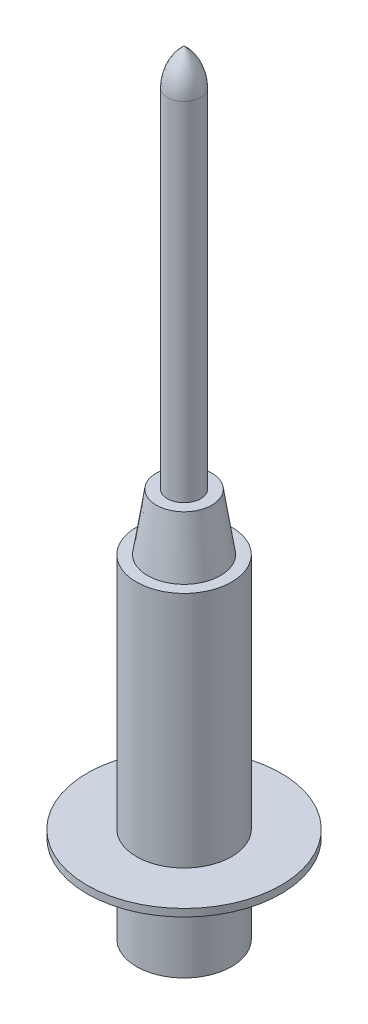
SolidWorks part; units mm, degrees
ref_plane "Front Plane" through (0, 0, 0) normal (0, 0, 1) x (1, 0, 0)
ref_plane "Top Plane" through (0, 0, 0) normal (0, 1, 0) x (1, 0, 0)
ref_plane "Right Plane" through (0, 0, 0) normal (1, 0, 0) x (0, 0, -1)
sketch "Sketch1" plane through (0, 0, 0) normal (0, 0, 1) x (1, 0, 0)
  line L0 (0, 0) -> (4.2806, 0)
  line L2 (4.2806, 29.97) -> (3.2806, 29.97)
  line L5 (1.5, 35.07) -> (1.5, 66.3238)
  line L6 (0, 69.5986) -> (0, 0) construction
  line L8 (4.2806, 0) -> (4.2806, 7.9)
  line L9 (4.2806, 7.9) -> (8.7329, 7.9)
  line L10 (8.7329, 7.9) -> (8.7329, 8.57)
  line L11 (8.7329, 8.57) -> (4.2806, 8.57)
  line L12 (4.2806, 8.57) -> (4.2806, 29.97)
  line L13 (3.2806, 29.97) -> (2.5, 35.07)
  line L14 (2.5, 35.07) -> (1.5, 35.07)
  line L15 (0, 69.5986) -> (0, 0)
  arc A0 (1.5, 66.3238) -> (0, 69.5986) centre (-2.8247, 66.3238) ccw
  dimension "D1" = 7.9
  dimension "D2" = 0.67
  dimension "D3" = 21.4
  dimension "D4" = 1
  dimension "D5" = 1
  dimension "D6" = 5.1
  dimension "D7" = 1.5
revolve "Revolve1" add sketch "Sketch1" angle 360 about L15
